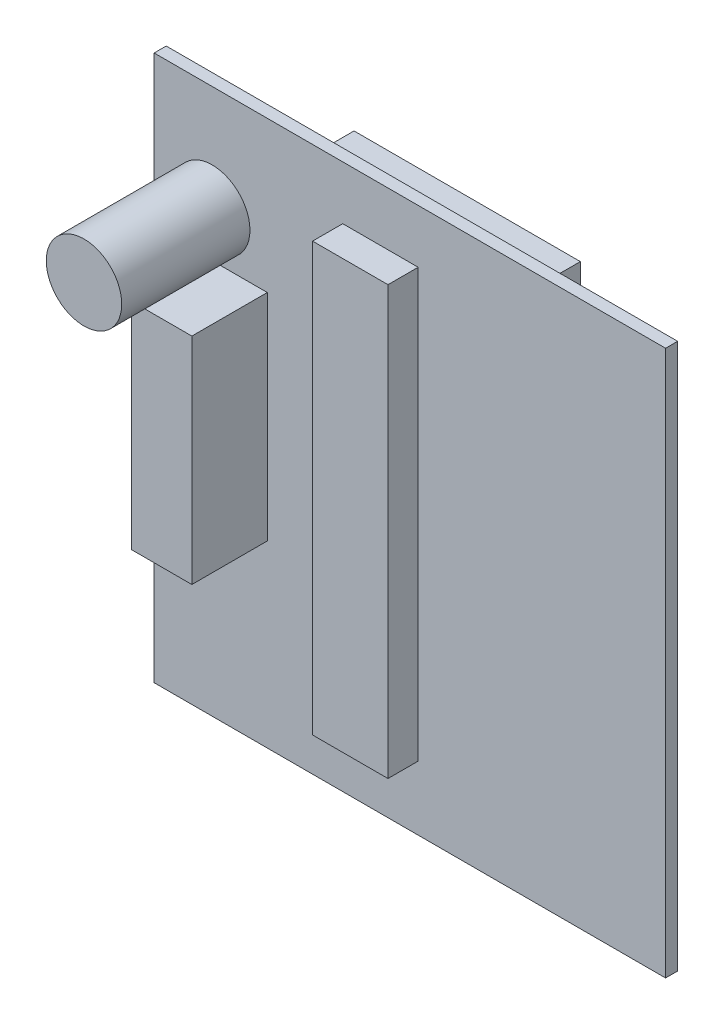
SolidWorks part; units mm, degrees
ref_plane "Front Plane" through (0, 0, 0) normal (0, 0, 1) x (1, 0, 0)
ref_plane "Top Plane" through (0, 0, 0) normal (0, 1, 0) x (1, 0, 0)
ref_plane "Right Plane" through (0, 0, 0) normal (1, 0, 0) x (0, 0, -1)
sketch "Sketch1" plane through (0, 0, 0) normal (0, 0, 1) x (1, 0, 0)
  line L1 (-38.1786, 53.9348) -> (29.6214, 53.9348)
  line L2 (-38.1786, 53.9348) -> (-38.1786, -18.3652)
  line L3 (-38.1786, -18.3652) -> (29.6214, -18.3652)
  line L4 (29.6214, 53.9348) -> (29.6214, -18.3652)
  dimension "D1" = 67.8
  dimension "D2" = 72.3
extrude "Boss-Extrude1" add sketch "Sketch1" along normal blind 1.6
sketch "Sketch3" plane through (0, 0, 1.6) normal (0, 0, 1) x (1, 0, 0)
  line L0 (29.6214, 53.9348) -> (-38.1786, 53.9348) construction
  line L1 (-3.1786, 46.8348) -> (-13.1786, 46.8348)
  line L2 (-3.1786, 46.8348) -> (-3.1786, -9.8651)
  line L3 (-3.1786, -9.8651) -> (-13.1786, -9.8651)
  line L4 (-13.1786, 46.8348) -> (-13.1786, -9.8651)
  line L5 (-38.1786, 53.9348) -> (-38.1786, -18.3652) construction
  dimension "D1" = 7.1
  dimension "D2" = 10
  dimension "D3" = 25
extrude "Boss-Extrude2" add sketch "Sketch3" along normal blind 4
sketch "Sketch4" plane through (0, 0, 1.6) normal (0, 0, 1) x (1, 0, 0)
  line L0 (29.6214, 53.9348) -> (-38.1786, 53.9348) construction
  line L1 (-31.1786, 33.9348) -> (-23.1786, 33.9348)
  line L2 (-31.1786, 33.9348) -> (-31.1786, 5.4094)
  line L3 (-31.1786, 5.4094) -> (-23.1786, 5.4094)
  line L4 (-23.1786, 33.9348) -> (-23.1786, 5.4094)
  line L5 (-38.1786, 53.9348) -> (-38.1786, -18.3652) construction
  line L6 (-38.1786, -18.3652) -> (29.6214, -18.3652) construction
  dimension "D1" = 8
  dimension "D2" = 20
  dimension "D3" = 7
  dimension "D4" = 23.7747
extrude "Boss-Extrude3" add sketch "Sketch4" along normal blind 10
sketch "Sketch5" plane through (0, 0, 1.6) normal (0, 0, 1) x (1, 0, 0)
  line L0 (29.6214, 53.9348) -> (-38.1786, 53.9348) construction
  line L1 (-38.1786, 53.9348) -> (-38.1786, -18.3652) construction
  circle A0 centre (-30.4786, 39.9348) radius 5
  point P6 (0, 0)
  dimension "D1" = 10
  dimension "D2" = 14
  dimension "7.7" = 7.7
extrude "Boss-Extrude4" add sketch "Sketch5" along normal blind 17
sketch "Sketch6" plane through (0, 0, 0) normal (0, 0, -1) x (-1, 0, 0)
  line L0 (38.1786, -18.3652) -> (-29.6214, -18.3652) construction
  line L1 (23.2786, -12.6652) -> (-6.7214, -12.6652)
  line L2 (23.2786, -12.6652) -> (23.2786, 46.6348)
  line L3 (23.2786, 46.6348) -> (-6.7214, 46.6348)
  line L4 (-6.7214, -12.6652) -> (-6.7214, 46.6348)
  line L5 (-29.6214, -18.3652) -> (-29.6214, 53.9348) construction
  dimension "D1" = 59.3
  dimension "D2" = 30
  dimension "D3" = 5.7
  dimension "D4" = 22.9
extrude "Boss-Extrude5" add sketch "Sketch6" along normal blind 10
